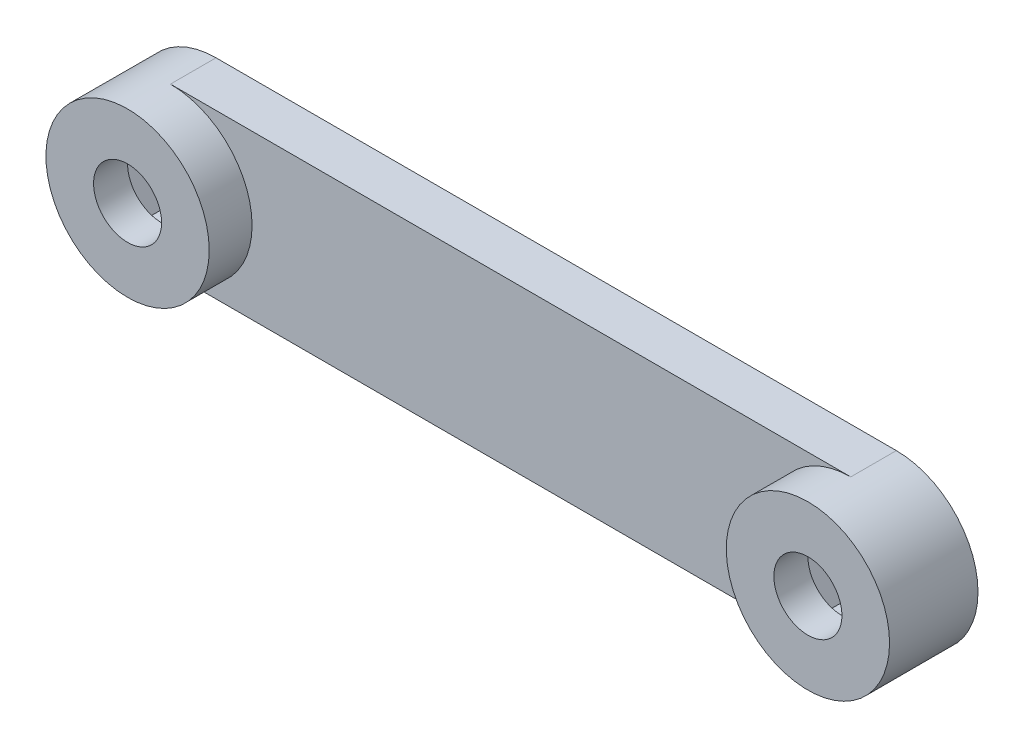
SolidWorks part; units mm, degrees
ref_plane "Front Plane" through (0, 0, 0) normal (0, 0, 1) x (1, 0, 0)
ref_plane "Top Plane" through (0, 0, 0) normal (0, 1, 0) x (1, 0, 0)
ref_plane "Right Plane" through (0, 0, 0) normal (1, 0, 0) x (0, 0, -1)
sketch "Sketch1" plane through (0, 0, 0) normal (0, 0, 1) x (1, 0, 0)
  line L0 (25, 0) -> (-25, 0) construction
  line L1 (-25, -6) -> (25, -6)
  line L2 (-25, 6) -> (25, 6)
  arc A0 (25, -6) -> (25, 6) centre (25, 0) ccw
  arc A1 (-25, 6) -> (-25, -6) centre (-25, 0) ccw
  circle A4 centre (-25, 0) radius 2.5
  circle A5 centre (25, 0) radius 2.5
  point P5 (0, 0)
  dimension "D3" = 12
  dimension "D2" = 5
  dimension "D1" = 50
extrude "Boss-Extrude1" add sketch "Sketch1" along normal blind 3.35
sketch "Sketch2" plane through (0, 0, 3.35) normal (0, 0, 1) x (1, 0, 0)
  circle A0 centre (-25, 0) radius 6
  circle A1 centre (25, 0) radius 6
  circle A2 centre (25, 0) radius 2.5 construction
  circle A3 centre (-25, 0) radius 2.5 construction
  circle A4 centre (25, 0) radius 2.5
  circle A5 centre (-25, 0) radius 2.5
extrude "Boss-Extrude2" add sketch "Sketch2" along normal blind 3.15
sketch "Sketch3" plane through (0, 0, 0) normal (0, 0, -1) x (-1, 0, 0)
  line L0 (0, 15.5436) -> (0, -16.1018) construction
  line L13 (20.4389, 0) -> (22.7195, 3.95)
  line L14 (-22.7195, 3.95) -> (-27.2805, 3.95)
  line L15 (-27.2805, 3.95) -> (-29.5611, 0)
  line L16 (-29.5611, 0) -> (-27.2805, -3.95)
  line L17 (-27.2805, -3.95) -> (-22.7195, -3.95)
  line L18 (-22.7195, -3.95) -> (-20.4389, 0)
  line L19 (-20.4389, 0) -> (-22.7195, 3.95)
  line L20 (22.7195, -3.95) -> (20.4389, 0)
  line L21 (27.2805, -3.95) -> (22.7195, -3.95)
  line L22 (29.5611, 0) -> (27.2805, -3.95)
  line L23 (27.2805, 3.95) -> (29.5611, 0)
  line L24 (22.7195, 3.95) -> (27.2805, 3.95)
  circle A2 centre (-25, 0) radius 3.95 construction
  circle A4 centre (25, 0) radius 3.95 construction
  dimension "D1" = 7.9
extrude "Cut-Extrude1" cut sketch "Sketch3" against normal blind 4
